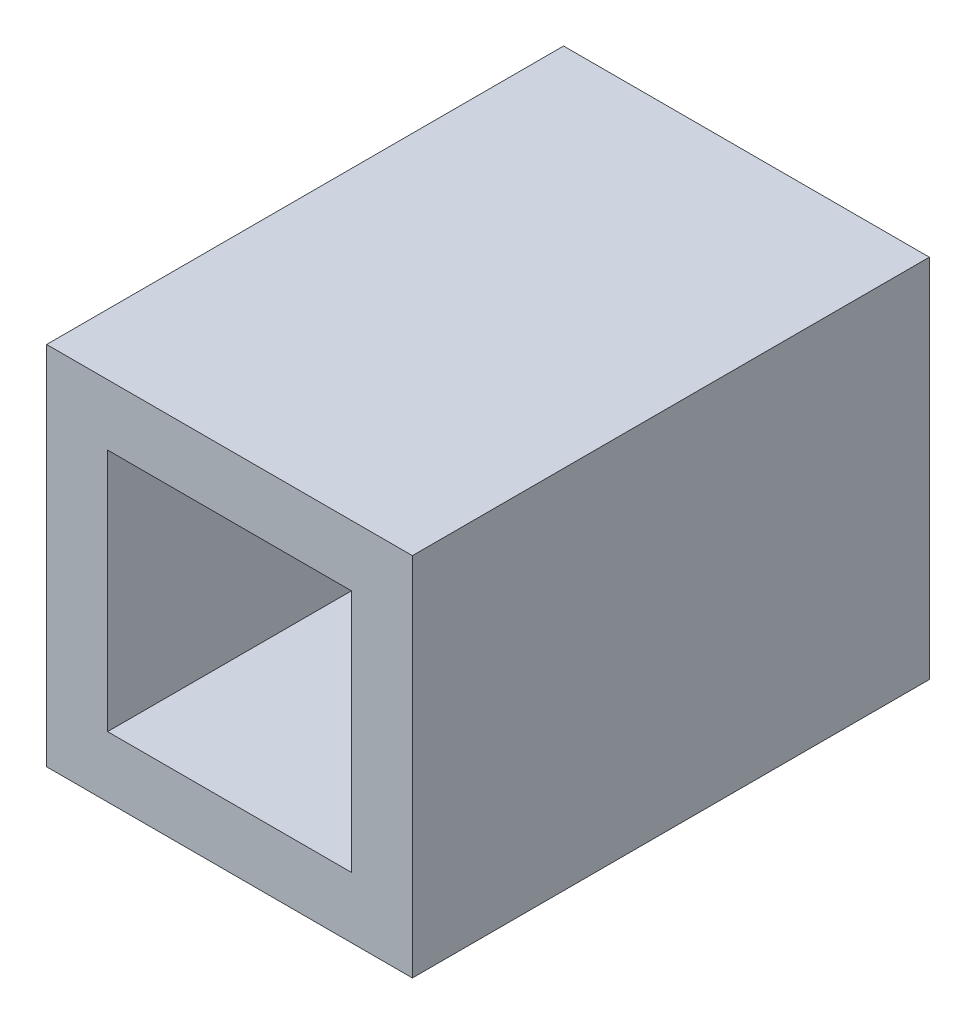
SolidWorks part; units mm, degrees
material "6061-T6 (SS)"
ref_plane "Front Plane" through (0, 0, 0) normal (0, 0, 1) x (1, 0, 0)
ref_plane "Top Plane" through (0, 0, 0) normal (0, 1, 0) x (1, 0, 0)
ref_plane "Right Plane" through (0, 0, 0) normal (1, 0, 0) x (0, 0, -1)
sketch "Sketch1" plane through (0, 0, 0) normal (0, 0, 1) x (1, 0, 0)
  line L1 (-15, 15) -> (15, 15)
  line L2 (-15, 15) -> (-15, -15)
  line L3 (-15, -15) -> (15, -15)
  line L4 (15, 15) -> (15, -15)
  line L5 (-15, 15) -> (15, -15) construction
  line L6 (-15, -15) -> (15, 15) construction
  line L7 (-10, 10) -> (10, 10)
  line L8 (-10, 10) -> (-10, -10)
  line L9 (-10, -10) -> (10, -10)
  line L10 (10, 10) -> (10, -10)
  line L11 (-10, 10) -> (10, -10) construction
  line L12 (-10, -10) -> (10, 10) construction
  point P0 (0, 0)
  point P6 (0, 0)
  dimension "D1" = 30
  dimension "D2" = 30
  dimension "D3" = 5
extrude "Boss-Extrude1" add sketch "Sketch1" along normal blind 42.4
